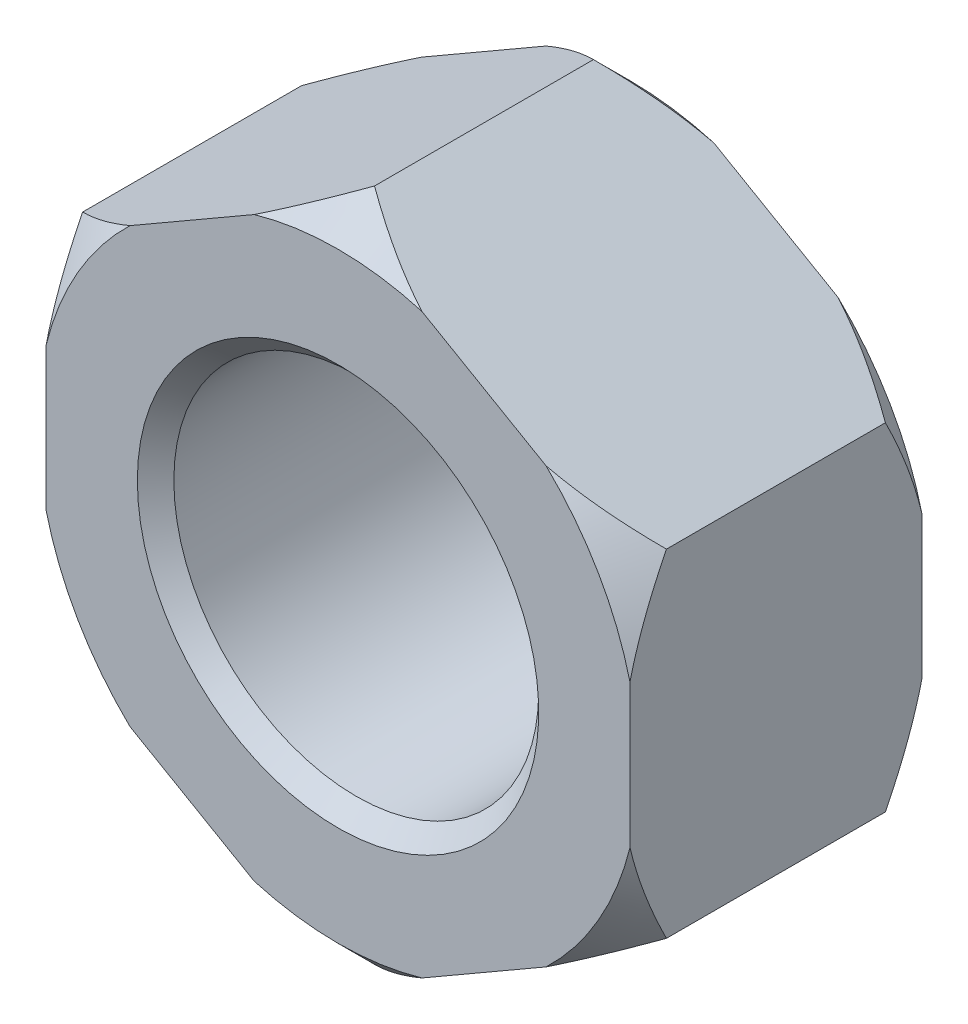
SolidWorks part; units mm, degrees
ref_plane "Спереди" through (0, 0, 0) normal (0, 0, 1) x (1, 0, 0)
ref_plane "Сверху" through (0, 0, 0) normal (0, 1, 0) x (1, 0, 0)
ref_plane "Справа" through (0, 0, 0) normal (1, 0, 0) x (0, 0, -1)
sketch "Эскиз1" plane through (0, 0, 0) normal (0, 0, 1) x (1, 0, 0)
  line L0 (0, 3.7738) -> (0, -4.1898) construction
  line L1 (-3.4469, 0) -> (3.2389, 0) construction
  line L3 (0, 4.6188) -> (-4, 2.3094)
  line L4 (-4, 2.3094) -> (-4, -2.3094)
  line L5 (-4, -2.3094) -> (0, -4.6188)
  line L6 (0, -4.6188) -> (4, -2.3094)
  line L7 (4, -2.3094) -> (4, 2.3094)
  line L8 (4, 2.3094) -> (0, 4.6188)
  circle A0 centre (0, 0) radius 4 construction
extrude "Вытянуть1" add sketch "Эскиз1" along normal blind 4
sketch "Эскиз2" plane through (0, 0, 0) normal (0, 0, -1) x (-1, 0, 0)
  circle A0 centre (0, 0) radius 2.5
ref_axis "Ось4" through (0, 0, 2.6338) along (0, 0, -1)
sketch "Эскиз15" plane through (0, 0, 0) normal (1, 0, 0) x (0, 0, -1)
  line L0 (-4, 4.6188) -> (-4, 4.1188)
  line L1 (-4, 2.3094) -> (-4, 4.6188) construction
  line L2 (-4, 4.1188) -> (-3.5, 4.6188)
  line L3 (-4, 4.6188) -> (0, 4.6188) construction
  line L4 (-3.5, 4.6188) -> (-4, 4.6188)
  line L5 (-0.5, 4.6188) -> (0, 4.6188)
  line L6 (0, 4.6188) -> (0, 4.1188)
  line L7 (0, 4.1188) -> (-0.5, 4.6188)
revolve "Вырез-Повернуть1" cut sketch "Эскиз15" angle 360 about axis through (0, 0, 2.6338) along (0, 0, -1)
ref_plane "Плоскость1" through (4, 0.9821, 4) normal (-0.2384, 0.9712, 0) x (-0.9712, -0.2384, 0)
extrude "Вырез-Вытянуть1" cut sketch "Эскиз2" against normal through all
chamfer "Фаска1" distance 0.25 angle 45 2 edges at (-2.5, 0, 0) (-2.5, 0, 4)
